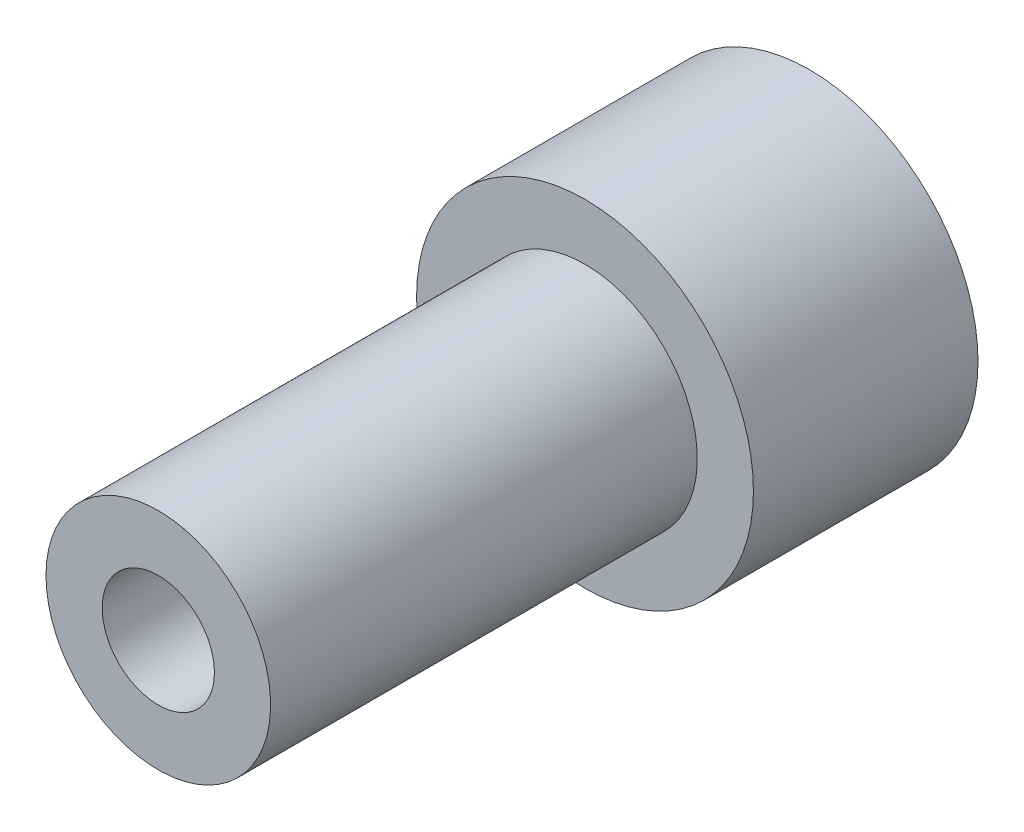
SolidWorks part; units mm, degrees
ref_plane "Ön Düzlem" through (0, 0, 0) normal (0, 0, 1) x (1, 0, 0)
ref_plane "Üst Düzlem" through (0, 0, 0) normal (0, 1, 0) x (1, 0, 0)
ref_plane "Sağ Düzlem" through (0, 0, 0) normal (1, 0, 0) x (0, 0, -1)
sketch "Sketch1" plane through (0, 0, 0) normal (0, 0, 1) x (1, 0, 0)
  circle A0 centre (0, 0) radius 7.5
  dimension "D1" = 15
extrude "Boss-Extrude1" add sketch "Sketch1" along normal blind 250
sketch "Sketch2" plane through (0, 0, 0) normal (0, 0, 1) x (1, 0, 0)
  circle A0 centre (0, 0) radius 5
  dimension "D1" = 10
extrude "Cut-Extrude1" cut sketch "Sketch2" along normal blind 10
ref_plane "Plane1" through (0, 0, 20) normal (0, 0, -1) x (-1, 0, 0)
sketch "Sketch3" plane through (0, 0, 10) normal (0, 0, -1) x (-1, 0, 0)
  circle A0 centre (0, 0) radius 5
  circle A1 centre (0, 0) radius 9.435
extrude "Cut-Extrude2" cut sketch "Sketch3" against normal blind 19
sketch "Sketch5" plane through (0, 0, 29) normal (0, 0, -1) x (-1, 0, 0)
  circle A0 centre (0, 0) radius 25.7657
extrude "Cut-Extrude3" cut sketch "Sketch5" against normal up to surface (221 mm away) up to face at (7.5, 0, 250)
sketch "Sketch6" plane through (0, 0, 10) normal (0, 0, -1) x (-1, 0, 0)
  circle A0 centre (0, 0) radius 6.0153
extrude "Boss-Extrude2" add sketch "Sketch6" along normal blind 10
sketch "Sketch7" plane through (0, 0, 29) normal (0, 0, 1) x (1, 0, 0)
  circle A0 centre (0, 0) radius 2.5
  dimension "D1" = 5
extrude "Cut-Extrude4" cut sketch "Sketch7" against normal blind 10
